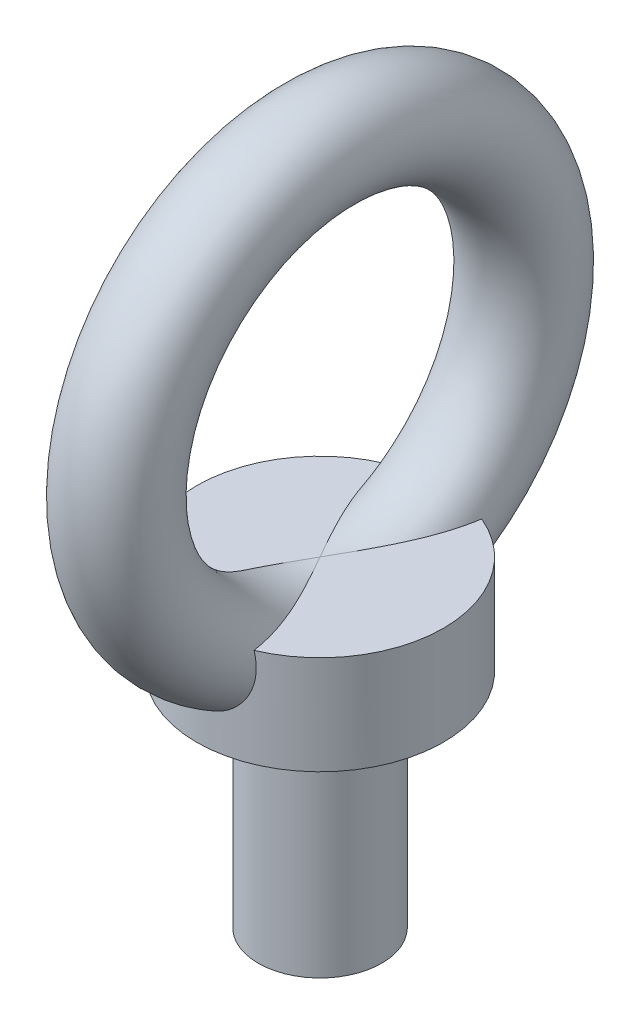
SolidWorks part; units mm, degrees
ref_plane "前基準面" through (0, 0, 0) normal (0, 0, 1) x (1, 0, 0)
ref_plane "上基準面" through (0, 0, 0) normal (0, 1, 0) x (1, 0, 0)
ref_plane "右基準面" through (0, 0, 0) normal (1, 0, 0) x (0, 0, -1)
sketch "草圖1" plane through (0, 0, 0) normal (0, 1, 0) x (1, 0, 0)
  circle A0 centre (0, 0) radius 5
  dimension "D1" = 10
extrude "填料-伸長1" add sketch "草圖1" along normal blind 18
sketch "草圖2" plane through (0, 18, 0) normal (0, 1, 0) x (1, 0, 0)
  circle A0 centre (0, 0) radius 10
  dimension "D1" = 20
extrude "填料-伸長2" add sketch "草圖2" along normal blind 8
sketch3d "3D草圖1"
  line L0 (0, 0, 0) -> (0, 22, 0)
  line L2 (0, 38.5, 0) -> (-5.54, 38.5, 0)
  circle A0 centre (0, 22, 0) radius 4
  point P4 (0, 22, 4)
  dimension "D2" = 8
  dimension "D1" = 22
  dimension "D3" = 16.5
sketch3d "3D草圖2" plane through (0, 0, 0) normal (0, 0, 1) x (1, 0, 0)
revolve "旋轉1" add sketch "3D草圖1" angle 360 about L2
